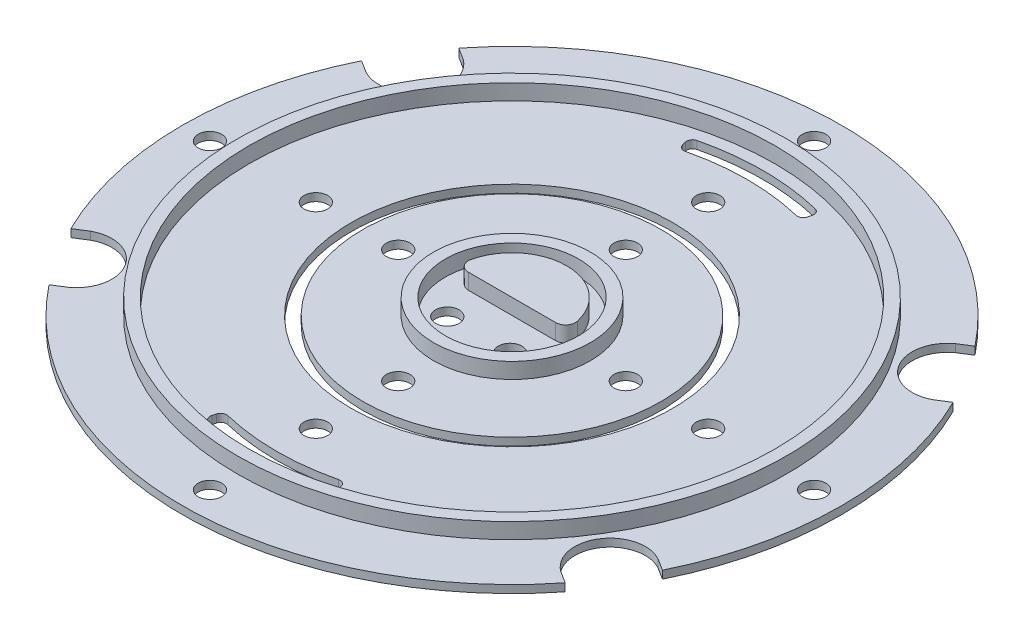
SolidWorks part; units mm, degrees
ref_plane "Front Plane" through (0, 0, 0) normal (0, 0, 1) x (1, 0, 0)
ref_plane "Top Plane" through (0, 0, 0) normal (0, 1, 0) x (1, 0, 0)
ref_plane "Right Plane" through (0, 0, 0) normal (1, 0, 0) x (0, 0, -1)
sketch "Эскиз1" plane through (0, 0, 0) normal (0, 1, 0) x (1, 0, 0)
  circle A0 centre (0, 0) radius 35
extrude "Бобышка-Вытянуть1" add sketch "Эскиз1" along normal blind 2
sketch "Эскиз2" plane through (0, 2, 0) normal (0, 1, 0) x (1, 0, 0)
  line L0 (0, 0) -> (-24.7487, 24.7487) construction
  line L17 (5.5656, 0) -> (-5.5656, 0)
  arc A2 (6.797, 1.542) -> (5.5656, 0) centre (5.5656, 1.2626) cw
  arc A17 (-6.797, 1.542) -> (6.797, 1.542) centre (0, 0) cw
  arc A18 (-5.5656, 0) -> (-6.797, 1.542) centre (-5.5656, 1.2626) cw
  circle A19 centre (0, 0) radius 8.4903
  circle A20 centre (0, 0) radius 10
  circle A21 centre (0, 0) radius 35 construction
  circle A30 centre (0, 0) radius 35
  circle A31 centre (0, 0) radius 33.5
  point P34 (0, 0.8588)
  dimension "D1" = 16.9805
  dimension "D2" = 20
  dimension "D4" = 1.2626
  dimension "D5" = 6.9697
extrude "Вырез-Вытянуть1" cut sketch "Эскиз2" against normal blind 2
sketch "Эскиз5" plane through (0, 0, 0) normal (0, -1, 0) x (1, 0, 0)
  circle A0 centre (0, 0) radius 42
  circle A1 centre (0, 0) radius 35 construction
  dimension "D1" = 84
extrude "Бобышка-Вытянуть3" add sketch "Эскиз5" along normal blind 2
sketch "Эскиз6" plane through (0, -2, 0) normal (0, -1, 0) x (1, 0, 0)
  line L35 (0, 0) -> (0, 10.135) construction
  line L36 (0, 0) -> (14.4718, 0) construction
  line L37 (37.6937, 18.5196) -> (37.6958, 18.5209)
  line L38 (36.1561, 17.5501) -> (37.6937, 18.5196)
  line L48 (-31.3628, 25.1463) -> (-32.8957, 26.1127)
  line L49 (-36.1561, 17.5501) -> (-37.6937, 18.5196)
  line L50 (31.3628, 25.1463) -> (32.8957, 26.1127)
  line L51 (-37.6937, -18.5196) -> (-37.6958, -18.5209)
  line L52 (-37.6937, 18.5196) -> (-37.6958, 18.5209)
  line L53 (31.3628, -25.1463) -> (32.8957, -26.1127)
  line L54 (-36.1561, -17.5501) -> (-37.6937, -18.5196)
  line L55 (-31.3628, -25.1463) -> (-32.8957, -26.1127)
  line L56 (36.1561, -17.5501) -> (37.6937, -18.5196)
  line L57 (37.6937, -18.5196) -> (37.6958, -18.5209)
  arc A53 (-36.1561, 17.5501) -> (-31.3628, 25.1463) centre (-34, 21.5) ccw
  arc A54 (32.8957, 26.1127) -> (37.6958, 18.5209) centre (0, 0) cw
  arc A56 (-32.8957, 26.1127) -> (-37.6958, 18.5209) centre (0, 0) ccw
  arc A57 (36.1561, 17.5501) -> (31.3628, 25.1463) centre (34, 21.5) cw
  arc A58 (36.1561, -17.5501) -> (31.3628, -25.1463) centre (34, -21.5) ccw
  arc A59 (-32.8957, -26.1127) -> (-37.6958, -18.5209) centre (0, 0) cw
  arc A60 (32.8957, -26.1127) -> (37.6958, -18.5209) centre (0, 0) ccw
  arc A61 (-36.1561, -17.5501) -> (-31.3628, -25.1463) centre (-34, -21.5) cw
extrude "Вырез-Вытянуть3" cut sketch "Эскиз6" against normal up to surface (2 mm away) up to face at (0, 0, -1.9798)
sketch "Эскиз7" plane through (0, 0, 0) normal (0, 1, 0) x (1, 0, 0)
  line L0 (0, 0) -> (0, 25) construction
  line L1 (0, 0) -> (0, -8.4903) construction
  line L2 (0, 0) -> (25, 0) construction
  line L3 (0, 0) -> (-25, 0) construction
  line L5 (0, -23.5) -> (0, -25) construction
  line L6 (0, -4.2451) -> (4, -4.2451) construction
  line L7 (0, -4.2451) -> (-4, -4.2451) construction
  line L8 (5.5656, 0) -> (-5.5656, 0) construction
  circle A5 centre (0, 25) radius 1.5
  circle A6 centre (-25, 0) radius 1.5
  circle A7 centre (25, 0) radius 1.5
  circle A8 centre (0, -25) radius 1.5
  circle A10 centre (4, -4.2451) radius 1.5
  circle A11 centre (-4, -4.2451) radius 1.5
  dimension "D1" = 3
  dimension "D2" = 25
  dimension "D3" = 25
extrude "Вырез-Вытянуть4" cut sketch "Эскиз7" against normal up to surface (2 mm away) up to face at (0, -2, 0)
sketch "Эскиз9" plane through (0, 0, 0) normal (0, 1, 0) x (1, 0, 0)
  line L0 (-4.2875, -42.5446) -> (27.7125, -42.5446) construction
  line L1 (0, 0) -> (-15.5268, 0) construction
  line L2 (-7.9563, -29.6934) -> (-8.0858, -30.1765)
  line L3 (7.9563, -29.6934) -> (8.0858, -30.1765)
  line L4 (7.9563, 29.6934) -> (8.0858, 30.1765)
  line L5 (-7.9563, 29.6934) -> (-8.0858, 30.1765)
  arc A0 (-7.538, -31.0995) -> (7.538, -31.0995) centre (0, 0) ccw
  arc A1 (-7.0555, -29.1585) -> (7.0555, -29.1585) centre (0, 0) ccw
  arc A2 (8.0858, -30.1765) -> (7.538, -31.0995) centre (7.3613, -30.3706) cw
  arc A3 (7.9563, -29.6934) -> (7.0555, -29.1585) centre (7.2319, -29.8875) ccw
  arc A4 (-7.538, -31.0995) -> (-8.0858, -30.1765) centre (-7.3613, -30.3706) cw
  arc A5 (-7.9563, -29.6934) -> (-7.0555, -29.1585) centre (-7.2319, -29.8875) cw
  arc A6 (-7.9563, 29.6934) -> (-7.0555, 29.1585) centre (-7.2319, 29.8875) ccw
  arc A7 (-7.538, 31.0995) -> (-8.0858, 30.1765) centre (-7.3613, 30.3706) ccw
  arc A8 (7.9563, 29.6934) -> (7.0555, 29.1585) centre (7.2319, 29.8875) cw
  arc A9 (8.0858, 30.1765) -> (7.538, 31.0995) centre (7.3613, 30.3706) ccw
  arc A10 (-7.0555, 29.1585) -> (7.0555, 29.1585) centre (0, 0) cw
  arc A11 (-7.538, 31.0995) -> (7.538, 31.0995) centre (0, 0) cw
  point P27 (-8.2822, 30.9096)
  point P28 (8.2822, 30.9096)
  dimension "D1" = 0.75
extrude "Вырез-Вытянуть5" cut sketch "Эскиз9" against normal up to surface (2 mm away) up to face at (0, -2, -26.5)
sketch "Эскиз10" plane through (0, 0, 0) normal (0, 1, 0) x (1, 0, 0)
  circle A0 centre (0, 0) radius 19
  circle A1 centre (0, 0) radius 20.5
  dimension "D1" = 38
  dimension "D2" = 41
extrude "Вырез-Вытянуть6" cut sketch "Эскиз10" against normal up to surface (2 mm away) up to face at (0, -2, 30.2327)
sketch "Эскиз11" plane through (0, 0, 0) normal (0, 1, 0) x (1, 0, 0)
  line L0 (0, 0) -> (0, 14.5) construction
  circle A0 centre (0, 14.5) radius 1.5
  circle A1 centre (14.5, 0) radius 1.5
  circle A2 centre (0, -14.5) radius 1.5
  circle A3 centre (-14.5, 0) radius 1.5
  point P13 (0, 0)
  dimension "D1" = 4
  dimension "D2" = 3
  dimension "D3" = 21.297
extrude "Вырез-Вытянуть7" cut sketch "Эскиз11" against normal up to surface (2 mm away) up to face at (4, -2, 2.7451)
sketch "Эскиз12" plane through (0, 0, 0) normal (0, 1, 0) x (1, 0, 0)
  circle A6 centre (0, -38.5) radius 1.5
  circle A7 centre (-38.5, 0) radius 1.5
  circle A8 centre (0, 38.5) radius 1.5
  circle A9 centre (38.5, 0) radius 1.5
  point P11 (0, 0)
  point P16 (0, 0)
extrude "Вырез-Вытянуть8" cut sketch "Эскиз12" against normal up to surface (2 mm away) up to face at (0, -2, -20.5)
sketch "Эскиз13" plane through (0, -2, 0) normal (0, -1, 0) x (1, 0, 0)
  circle A0 centre (0, 0) radius 42
extrude "Вырез-Вытянуть9" cut sketch "Эскиз13" against normal blind 1
sketch "Эскиз15" plane through (0, -1, 0) normal (0, -1, 0) x (1, 0, 0)
  circle A0 centre (21.9999, 21.9356) radius 2
  circle A1 centre (21.9999, -22.0642) radius 2
  circle A2 centre (-21.9999, -22.0642) radius 2
  circle A3 centre (-21.9999, 21.9358) radius 2
  circle A4 centre (-0.0001, 4.1858) radius 2
  point P8 (0, 0)
extrude "Бобышка-Вытянуть5" add sketch "Эскиз15" along normal blind 4
